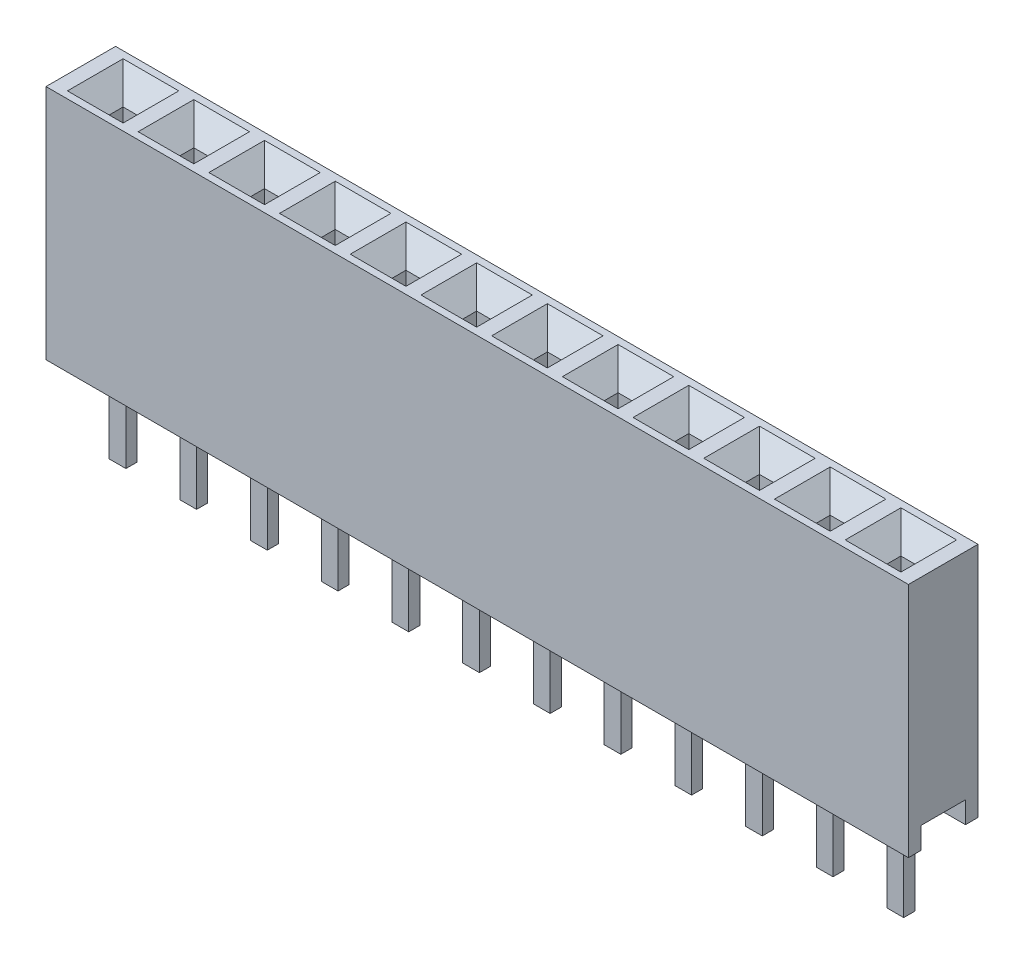
SolidWorks part; units mm, degrees
ref_plane "Спереди" through (0, 0, 0) normal (0, 0, 1) x (1, 0, 0)
ref_plane "Сверху" through (0, 0, 0) normal (0, 1, 0) x (1, 0, 0)
ref_plane "Справа" through (0, 0, 0) normal (1, 0, 0) x (0, 0, -1)
sketch "Эскиз1" plane through (0, 0, 0) normal (0, 1, 0) x (1, 0, 0)
  line L1 (-15.49, 1.25) -> (15.49, 1.25)
  line L2 (-15.49, 1.25) -> (-15.49, -1.25)
  line L3 (-15.49, -1.25) -> (15.49, -1.25)
  line L4 (15.49, 1.25) -> (15.49, -1.25)
  line L5 (-15.49, 1.25) -> (15.49, -1.25) construction
  line L6 (-15.49, -1.25) -> (15.49, 1.25) construction
  point P0 (0, 0)
  dimension "D1" = 2.5
  dimension "D2" = 30.98
extrude "Бобышка-Вытянуть1" add sketch "Эскиз1" along normal blind 8.5
sketch "Эскиз5" plane through (0, 8.5, 0) normal (0, 1, 0) x (1, 0, 0)
  line L0 (-13.97, 0) -> (13.97, 0)
  point P3 (0, 0)
  dimension "D1" = 27.94
sketch "Эскиз2" plane through (0, 8.5, 0) normal (0, 1, 0) x (1, 0, 0)
  line L7 (1.02, 0.25) -> (1.52, 0.25)
  line L8 (1.02, 0.25) -> (1.02, -0.25)
  line L9 (1.02, -0.25) -> (1.52, -0.25)
  line L10 (1.52, 0.25) -> (1.52, -0.25)
  line L11 (1.02, 0.25) -> (1.52, -0.25) construction
  line L12 (1.02, -0.25) -> (1.52, 0.25) construction
  point P5 (1.27, 0)
  point P10 (0, 0)
  point P13 (13.97, 0)
  dimension "D2" = 1.27
  dimension "D3" = 0.5
  dimension "D4" = 13.97
extrude "Вырез-Вытянуть1" cut sketch "Эскиз2" against normal offset from surface (7.5 mm away) 1 up to face at (0, 0, 0)
chamfer "Фаска1" distance 0.75 angle 45 4 edges at (1.02, 8.5, 0) (1.27, 8.5, 0.25) (1.52, 8.5, 0) (1.27, 8.5, -0.25)
sketch "Эскиз6" plane through (0, 8.5, 0) normal (0, 1, 0) x (1, 0, 0)
  line L1 (-1.52, 0.25) -> (-1.02, 0.25)
  line L2 (-1.52, 0.25) -> (-1.52, -0.25)
  line L3 (-1.52, -0.25) -> (-1.02, -0.25)
  line L4 (-1.02, 0.25) -> (-1.02, -0.25)
  line L5 (-1.52, 0.25) -> (-1.02, -0.25) construction
  line L6 (-1.52, -0.25) -> (-1.02, 0.25) construction
  point P0 (-1.27, 0)
  point P5 (0, 0)
  point P10 (0, 0)
  dimension "D1" = 1.27
extrude "Вырез-Вытянуть3" cut sketch "Эскиз6" against normal up to surface (7.5 mm away) up to face at (1.27, 1, 0)
chamfer "Фаска3" distance 0.75 angle 45 4 edges at (-1.02, 8.5, 0) (-1.27, 8.5, 0.25) (-1.52, 8.5, 0) (-1.27, 8.5, -0.25)
sketch "Эскиз4" plane through (15.49, 0, 0) normal (1, 0, 0) x (0, 0, -1)
  line L1 (-0.8, 0) -> (0.8, 0)
  line L2 (-0.8, 0) -> (-0.8, 0.7764)
  line L3 (-0.8, 0.7764) -> (0.8, 0.7764)
  line L4 (0.8, 0) -> (0.8, 0.7764)
  line L5 (-1.25, 0) -> (1.25, 0) construction
  point P6 (0, 0)
  dimension "D1" = 1.6
extrude "Вырез-Вытянуть2" cut sketch "Эскиз4" against normal up to next
sketch "Эскиз3" plane through (0, 0, 0) normal (0, -1, 0) x (1, 0, 0)
  line L0 (-2.79, 0) -> (2.79, 0) construction
  line L3 (0, 0) -> (0, 1.0405) construction
  line L4 (-1.57, 0.2) -> (-0.97, 0.2)
  line L5 (-1.57, 0.2) -> (-1.57, -0.2)
  line L6 (-1.57, -0.2) -> (-0.97, -0.2)
  line L7 (-0.97, 0.2) -> (-0.97, -0.2)
  line L8 (-1.57, 0.2) -> (-0.97, -0.2) construction
  line L9 (-1.57, -0.2) -> (-0.97, 0.2) construction
  line L10 (0.97, 0.2) -> (1.57, 0.2)
  line L11 (0.97, 0.2) -> (0.97, -0.2)
  line L12 (0.97, -0.2) -> (1.57, -0.2)
  line L13 (1.57, 0.2) -> (1.57, -0.2)
  line L14 (0.97, 0.2) -> (1.57, -0.2) construction
  line L15 (0.97, -0.2) -> (1.57, 0.2) construction
  point P3 (1.27, 0)
  point P4 (0, 0)
  point P9 (-1.27, 0)
  dimension "D1" = 2.54
  dimension "D2" = 0.6
  dimension "D3" = 0.4
pattern_linear "Линейный массив1" count 6 spacing 2.54 along (-1, 0, 0) of "Вырез-Вытянуть3", "Фаска3"
pattern_linear "Линейный массив2" count 6 spacing 2.54 along (1, 0, 0) of "Фаска1", "Вырез-Вытянуть1"
sketch "Эскиз7" plane through (0, 0.7764, 0) normal (0, -1, 0) x (1, 0, 0)
  line L0 (-1.57, 0.2) -> (-1.57, -0.2) construction
  line L1 (-1.57, 0.2) -> (-0.97, 0.2) construction
  line L2 (-0.97, 0.2) -> (-0.97, -0.2) construction
  line L3 (-1.57, -0.2) -> (-0.97, -0.2) construction
  line L12 (-1.57, 0.2) -> (-1.57, -0.2)
  line L13 (-1.57, 0.2) -> (-0.97, 0.2)
  line L14 (-0.97, 0.2) -> (-0.97, -0.2)
  line L15 (-1.57, -0.2) -> (-0.97, -0.2)
sketch "Эскиз8" plane through (0, 0.7764, 0) normal (0, -1, 0) x (1, 0, 0)
  line L0 (0.97, 0.2) -> (0.97, -0.2) construction
  line L1 (0.97, -0.2) -> (1.57, -0.2) construction
  line L2 (1.57, 0.2) -> (1.57, -0.2) construction
  line L3 (0.97, 0.2) -> (1.57, 0.2) construction
  line L12 (0.97, 0.2) -> (0.97, -0.2)
  line L13 (0.97, -0.2) -> (1.57, -0.2)
  line L14 (1.57, 0.2) -> (1.57, -0.2)
  line L15 (0.97, 0.2) -> (1.57, 0.2)
extrude "Бобышка-Вытянуть4" add sketch "Эскиз7" along normal offset from surface (3.7764 mm away) 3 separate body up to face at (0, 0, 1.025) offset beyond the face yes
chamfer "Фаска4" [suppressed] distance 0.2 angle 45
extrude "Бобышка-Вытянуть5" add sketch "Эскиз8" along normal offset from surface (3.7764 mm away) 3 separate body up to face at (0, 0, 1.025) offset beyond the face yes
chamfer "Фаска5" [suppressed] distance 0.2 angle 45
pattern_linear "Линейный массив8" count 6 spacing 2.54 along (1, 0, 0) of "Бобышка-Вытянуть5"
pattern_linear "Линейный массив9" count 6 spacing 2.54 along (-1, 0, 0) of "Бобышка-Вытянуть4"
equation "\"N\" = 12"
equation "\"D2@Эскиз1\"=\"N\"*2.54+0.5"
equation "\"D1@Эскиз5\"=(\"N\"-1)*2.54"
equation "\"D1@Линейный массив1\"=\"N\"/2"
equation "\"D1@Линейный массив2\"=\"N\"/2"
